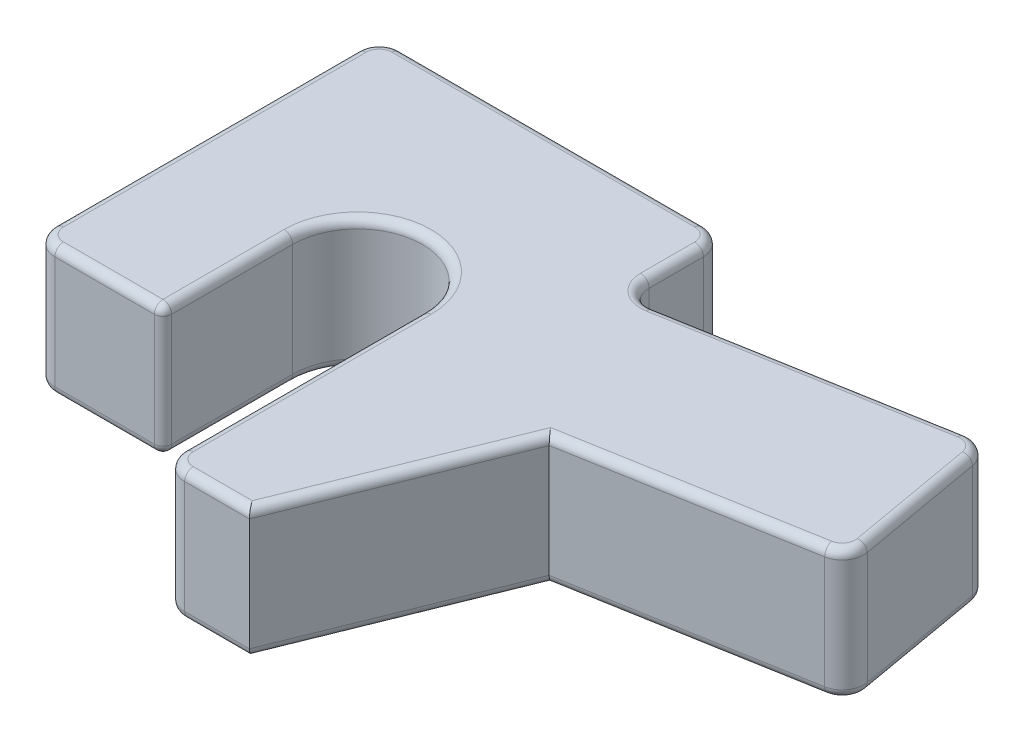
SolidWorks part; units mm, degrees
ref_plane "Front Plane" through (0, 0, 0) normal (0, 0, 1) x (1, 0, 0)
ref_plane "Top Plane" through (0, 0, 0) normal (0, 1, 0) x (1, 0, 0)
ref_plane "Right Plane" through (0, 0, 0) normal (1, 0, 0) x (0, 0, -1)
sketch "Sketch1" plane through (0, 0, 0) normal (0, 1, 0) x (1, 0, 0)
  line L0 (-1.5, 0) -> (-1.5, -3)
  line L1 (-1.5, -3) -> (-4, -3)
  line L2 (-4.5, -2.5) -> (-4.5, 4.5)
  line L3 (-4, 5) -> (3, 5)
  line L4 (3.5, 4.5) -> (3.5, 3.2439)
  line L5 (-1.5, -3) -> (-1.4499, -3.0179)
  line L6 (1.5, 0) -> (1.5, -5.5)
  line L7 (0, 0) -> (9.3162, 1.6427) construction
  line L8 (4.0868, 2.7515) -> (10.217, 3.8324)
  line L9 (10.7962, 3.4268) -> (11.3171, 0.4724)
  line L10 (10.9116, -0.1069) -> (5.4951, -1.0619)
  line L11 (5.4951, -1.0619) -> (3.5, -6)
  line L12 (3.5, -6) -> (2, -6)
  arc A0 (1.5, 0) -> (-1.5, 0) centre (0, 0) ccw
  arc A1 (11.3171, 0.4724) -> (10.9116, -0.1069) centre (10.8247, 0.3856) cw
  arc A2 (10.217, 3.8324) -> (10.7962, 3.4268) centre (10.3038, 3.34) cw
  arc A3 (1.5, -5.5) -> (2, -6) centre (2, -5.5) ccw
  arc A4 (-4, -3) -> (-4.5, -2.5) centre (-4, -2.5) cw
  arc A5 (-4.5, 4.5) -> (-4, 5) centre (-4, 4.5) cw
  arc A6 (3, 5) -> (3.5, 4.5) centre (3, 4.5) cw
  arc A7 (3.5, 3.2439) -> (4.0868, 2.7515) centre (4, 3.2439) ccw
  point P18 (11.404, -0.02)
  point P21 (10.7094, 3.9192)
  point P24 (1.5, -6)
  point P27 (-4.5, -3)
  point P30 (-4.5, 5)
  point P33 (3.5, 5)
  dimension "D1" = 3
  dimension "D13" = 0.5
  dimension "D2" = 3
  dimension "D3" = 8
  dimension "D4" = 3
  dimension "D5" = 6
  dimension "D6" = 10
  dimension "D7" = 4
  dimension "D8" = 2
  dimension "D9" = 8
  dimension "D10" = 6
  dimension "D11" = 2
  dimension "D12" = 22
extrude "Boss-Extrude1" add sketch "Sketch1" along normal blind 3 contours A0 L7 L9 A2 L8 A7 L4 A6 L3 A5 L2 A4 L1 L0 | L7 A0 L6 A3 L12 L11 L10 A1 L9
ref_plane "Plane1" through (0, 0, 0) normal (0, 0, 1) x (0, -1, 0)
fillet "Fillet1" radius 0.2 39 edges at (3.5, 0, -3.8719) (3.3536, 0, -4.8536) (-0.5, 0, -5) (-4.3536, 0, -4.8536) (-4.5, 0, -1) (-4.3536, 0, 2.8536) (-2.75, 0, 3) (-1.5, 0, 1.5) (0, 0, -1.5) (1.5, 0, 2.75) (1.6464, 0, 5.8536) (2.75, 0, 6) (4.4976, 0, 3.531) (8.2033, 0, 0.5844) (11.2343, 0, -0.0988) (11.0567, 0, -1.9496) (10.5906, 0, -3.7496) (7.1519, 0, -3.2919) (3.6786, 0, -2.8609) (7.1519, 3, -3.2919) (10.5906, 3, -3.7496) (11.0567, 3, -1.9496) (11.2343, 3, -0.0988) (8.2033, 3, 0.5844) (4.4976, 3, 3.531) (2.75, 3, 6) (1.6464, 3, 5.8536) (1.5, 3, 2.75) (0, 3, -1.5) (-1.5, 3, 1.5) (-2.75, 3, 3) (-4.3536, 3, 2.8536) (-4.5, 3, -1) (-4.3536, 3, -4.8536) (-0.5, 3, -5) (3.3536, 3, -4.8536) (3.5, 3, -3.8719) (3.6786, 3, -2.8609) (-1.5, 1.5, 3)
